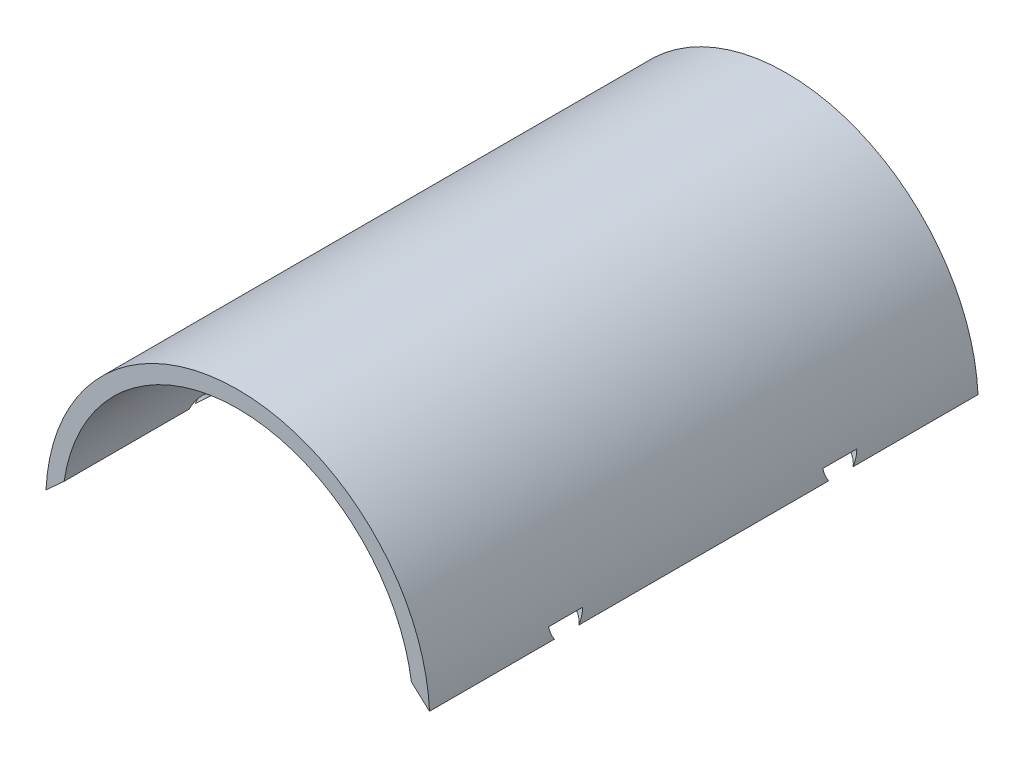
SolidWorks part; units mm, degrees
ref_plane "Front Plane" through (0, 0, 0) normal (0, 0, 1) x (1, 0, 0)
ref_plane "Top Plane" through (0, 0, 0) normal (0, 1, 0) x (1, 0, 0)
ref_plane "Right Plane" through (0, 0, 0) normal (1, 0, 0) x (0, 0, -1)
sketch "Sketch1" plane through (0, 0, 0) normal (0, 0, 1) x (1, 0, 0)
  line L0 (0, 0) -> (0, 44.45) construction
  line L1 (-40.2039, 5.9378) -> (40.2039, 5.9378) construction
  line L2 (-44.399, 2.1278) -> (44.399, 2.1278) construction
  line L3 (-40.2039, 5.9378) -> (-44.399, 2.1278)
  line L4 (40.2039, 5.9378) -> (44.399, 2.1278)
  arc A0 (44.399, 2.1278) -> (-44.399, 2.1278) centre (0, 0) ccw
  arc A1 (40.2039, 5.9378) -> (-40.2039, 5.9378) centre (0, 0) ccw
  dimension "D1" = 88.9
  dimension "D2" = 3.81
  dimension "D3" = 3.81
extrude "Boss-Extrude1" add sketch "Sketch1" along normal blind 127
sketch "Sketch2" plane through (-21.1272, 23.263, 0) normal (0.6723, -0.7403, 0) x (0.7403, 0.6723, 0)
  line L0 (-28.6033, 127) -> (-28.6033, 0.0141) construction
  line L1 (-31.4368, 127) -> (-25.7698, 127) construction
  line L2 (-31.4368, 63.5) -> (-25.7698, 63.5) construction
  line L3 (-31.4368, 127) -> (-31.4368, 0) construction
  line L4 (-25.7698, 127) -> (-25.7698, 0) construction
  circle A0 centre (-28.6033, 95.25) radius 4
  circle A1 centre (-28.6033, 31.75) radius 4
  dimension "D1" = 8
  dimension "D2" = 31.75
extrude "Cut-Extrude1" cut sketch "Sketch2" against normal blind 2
sketch "Sketch3" plane through (21.1272, 23.263, 0) normal (-0.6723, -0.7403, 0) x (0.7403, -0.6723, 0)
  line L0 (28.6033, 127) -> (28.6033, 0.2465) construction
  line L1 (25.7698, 127) -> (31.4368, 127) construction
  line L2 (25.7698, 63.5) -> (31.4368, 63.5) construction
  line L3 (25.7698, 127) -> (25.7698, 0) construction
  line L4 (31.4368, 127) -> (31.4368, 0) construction
  circle A0 centre (28.6033, 95.25) radius 4
  circle A1 centre (28.6033, 31.75) radius 4
  dimension "D1" = 8
  dimension "D2" = 31.75
extrude "Cut-Extrude2" cut sketch "Sketch3" against normal blind 2
